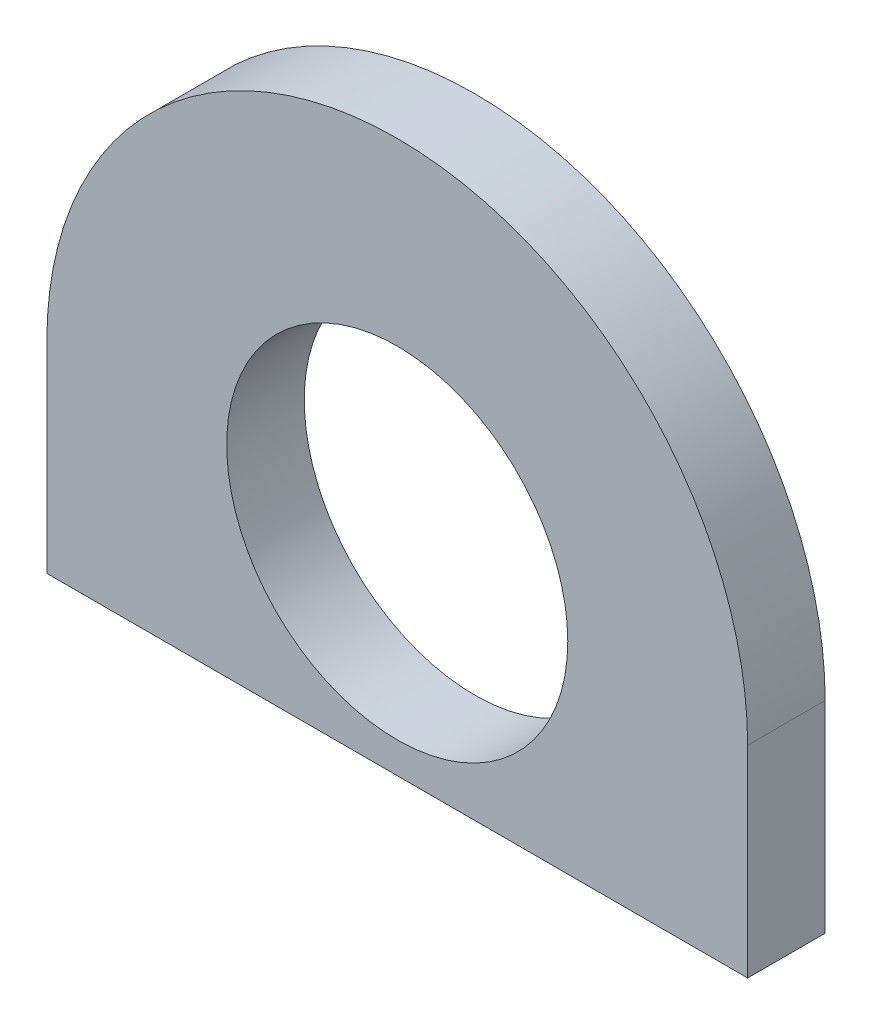
SolidWorks part; units mm, degrees
ref_plane "Front Plane" through (0, 0, 0) normal (0, 0, 1) x (1, 0, 0)
ref_plane "Top Plane" through (0, 0, 0) normal (0, 1, 0) x (1, 0, 0)
ref_plane "Right Plane" through (0, 0, 0) normal (1, 0, 0) x (0, 0, -1)
sketch "Sketch1" plane through (0, 0, 0) normal (0, 0, 1) x (1, 0, 0)
  line L1 (22.6, -13) -> (-22.6, -13)
  line L2 (22.6, -13) -> (22.6, 0)
  line L4 (-22.6, -13) -> (-22.6, 0)
  line L5 (22.6, -13) -> (-22.6, 0) construction
  line L6 (22.6, 0) -> (-22.6, -13) construction
  circle A0 centre (0, 0) radius 11
  arc A2 (22.6, 0) -> (-22.6, 0) centre (0, 0) ccw
  point P3 (0, -6.5)
  dimension "D1" = 22.6
  dimension "D2" = 22
extrude "Boss-Extrude1" add sketch "Sketch1" along normal blind 5
